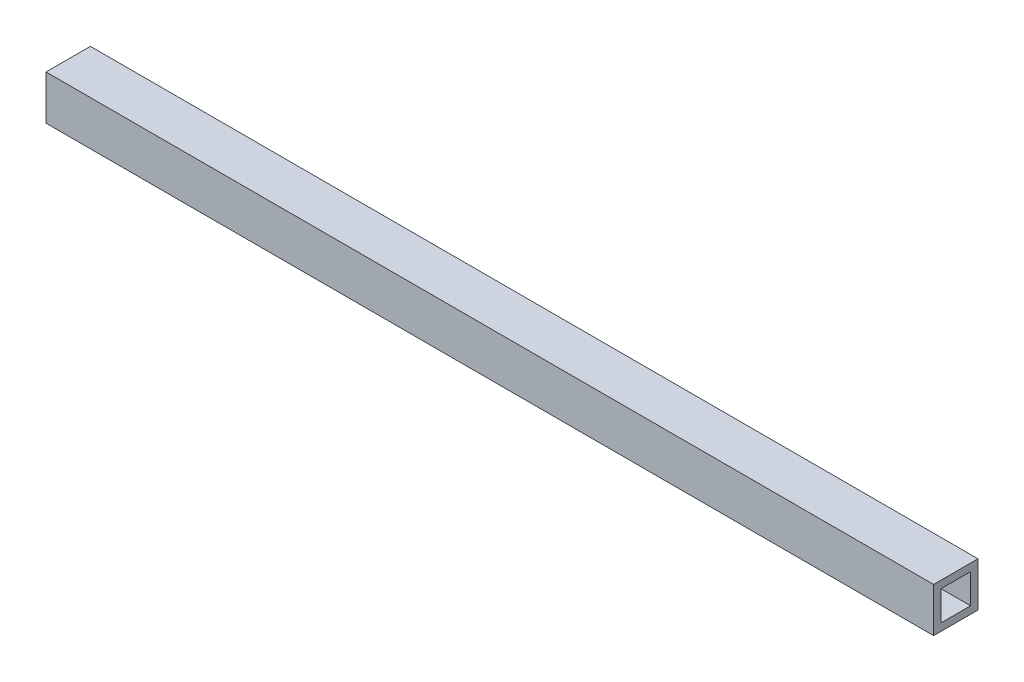
SolidWorks part; units mm, degrees
material "6061 Alloy"
ref_plane "Front Plane" through (0, 0, 0) normal (0, 0, 1) x (1, 0, 0)
ref_plane "Top Plane" through (0, 0, 0) normal (0, 1, 0) x (1, 0, 0)
ref_plane "Right Plane" through (0, 0, 0) normal (1, 0, 0) x (0, 0, -1)
sketch "Sketch1" plane through (0, 0, 0) normal (1, 0, 0) x (0, 0, -1)
  line L1 (-9.525, -9.525) -> (9.525, -9.525)
  line L2 (-9.525, -9.525) -> (-9.525, 9.525)
  line L3 (-9.525, 9.525) -> (9.525, 9.525)
  line L4 (9.525, -9.525) -> (9.525, 9.525)
  line L5 (-9.525, -9.525) -> (9.525, 9.525) construction
  line L6 (-9.525, 9.525) -> (9.525, -9.525) construction
  line L7 (6.35, -6.35) -> (-6.35, -6.35)
  line L8 (6.35, -6.35) -> (6.35, 6.35)
  line L9 (6.35, 6.35) -> (-6.35, 6.35)
  line L10 (-6.35, -6.35) -> (-6.35, 6.35)
  line L11 (6.35, -6.35) -> (-6.35, 6.35) construction
  line L12 (6.35, 6.35) -> (-6.35, -6.35) construction
  point P0 (0, 0)
  dimension "D1" = 19.05
  dimension "D2" = 19.05
  dimension "D3" = 3.175
  dimension "D4" = 3.175
extrude "Boss-Extrude1" add sketch "Sketch1" along normal mid plane 381
